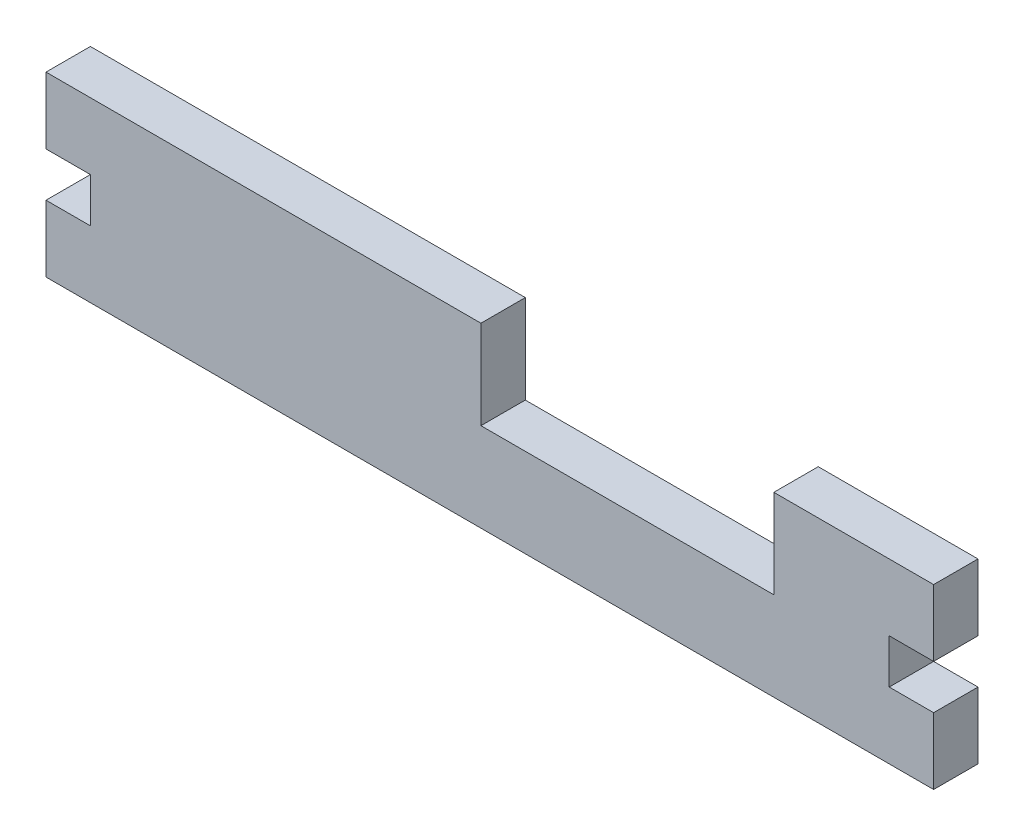
SolidWorks part; units mm, degrees
ref_plane "Plan de face" through (0, 0, 0) normal (0, 0, 1) x (1, 0, 0)
ref_plane "Plan de dessus" through (0, 0, 0) normal (0, 1, 0) x (1, 0, 0)
ref_plane "Plan de droite" through (0, 0, 0) normal (1, 0, 0) x (0, 0, -1)
sketch "Esquisse1" plane through (0, 0, 0) normal (0, 0, 1) x (1, 0, 0)
  line L0 (45, 0) -> (45, 20) construction
  line L1 (0, 0) -> (90, 0)
  line L2 (0, 7.5) -> (0, 12.5)
  line L3 (0, 20) -> (44, 20)
  line L4 (90, 7.5) -> (90, 12.5)
  line L5 (90, 0) -> (95, 0)
  line L6 (0, 20) -> (-5, 20)
  line L7 (77, 20) -> (90, 20)
  line L8 (0, 12.5) -> (-5, 12.5)
  line L9 (-5, 20) -> (-5, 12.5)
  line L10 (0, 0) -> (-5, 0)
  line L12 (0, 7.5) -> (-5, 7.5)
  line L13 (-5, 0) -> (-5, 7.5)
  line L14 (95, 0) -> (95, 7.5)
  line L15 (90, 7.5) -> (95, 7.5)
  line L16 (90, 12.5) -> (95, 12.5)
  line L17 (95, 20) -> (95, 12.5)
  line L18 (90, 20) -> (95, 20)
  line L19 (77, 20) -> (77, 10)
  line L20 (77, 10) -> (44, 10)
  line L21 (44, 20) -> (44, 10)
  dimension "D1" = 90
  dimension "D2" = 20
  dimension "D3" = 13
  dimension "D4" = 7.5
  dimension "D5" = 5
  dimension "D6" = 33
  dimension "D7" = 10
extrude "Boss.-Extru.1" add sketch "Esquisse1" along normal blind 5
